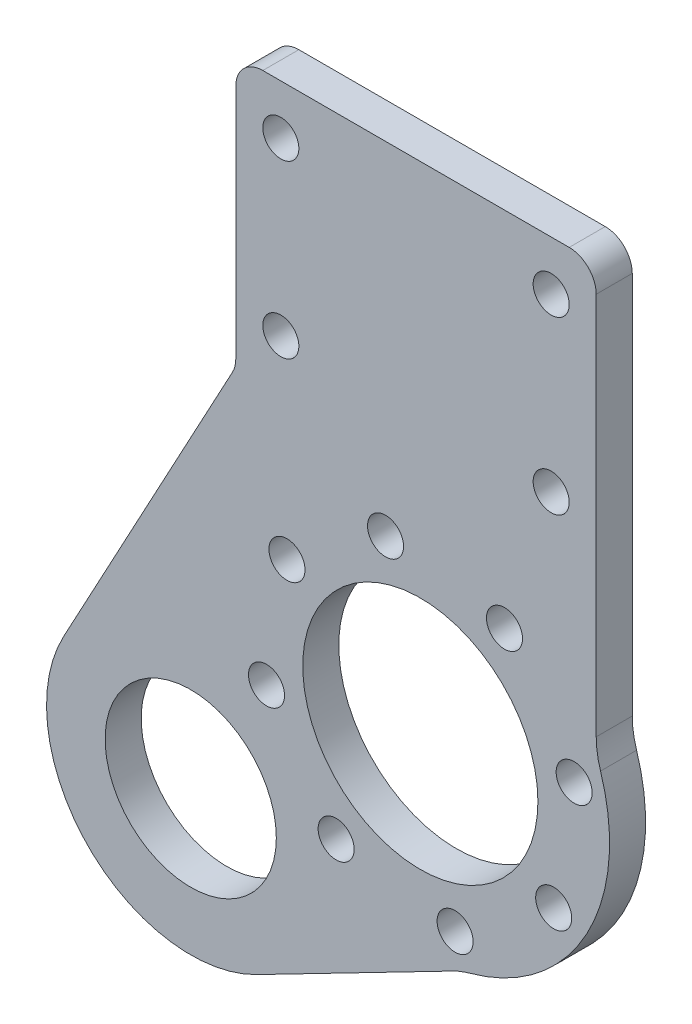
SolidWorks part; units mm, degrees
material "Thornel Mat VMA"
ref_plane "前视基准面" through (0, 0, 0) normal (0, 0, 1) x (1, 0, 0)
ref_plane "上视基准面" through (0, 0, 0) normal (0, 1, 0) x (1, 0, 0)
ref_plane "右视基准面" through (0, 0, 0) normal (1, 0, 0) x (0, 0, -1)
sketch "草图1" plane through (0, 0, 0) normal (0, 0, 1) x (1, 0, 0)
  line L0 (-30.2639, 43) -> (71.8423, 43) construction
  line L1 (-16, 73) -> (-16, 0)
  line L2 (-16, 73) -> (45, 73)
  line L3 (45, 73) -> (45, 18)
  line L4 (7.3324, -14.221) -> (33.6238, -0.665)
  circle A0 centre (0, 0) radius 10 construction
  arc A1 (33.6238, -0.665) -> (45, 18) centre (24, 18) ccw
  circle A2 centre (24, 18) radius 20 construction
  circle A3 centre (24, 18) radius 13.05
  circle A5 centre (0, 0) radius 9.5
  arc A6 (-16, 0) -> (7.3324, -14.221) centre (0, 0) ccw
  dimension "D1" = 20
  dimension "D2" = 42
  dimension "D3" = 40
  dimension "D5" = 4
  dimension "D6" = 26.1
  dimension "D8" = 16
  dimension "D9" = 19
  dimension "D4" = 43
  dimension "D7" = 30
extrude "凸台-拉伸1" add sketch "草图1" along normal blind 4
fillet "圆角1" radius 3 2 edges at (45, 73, 2) (-16, 73, 2)
sketch "草图2" plane through (0, 0, 4) normal (0, 0, 1) x (1, 0, 0)
  line L0 (-14.0845, 7.5912) -> (5, 43)
  line L1 (5, 43) -> (5, 73)
  line L2 (42, 73) -> (-13, 73) construction
  line L4 (45, 18) -> (45, 70) construction
  line L5 (-16, 70) -> (-16, 0) construction
  line L6 (-16, 73) -> (-16, 0)
  line L7 (-16, 73) -> (5, 73)
  arc A1 (-14.0845, 7.5912) -> (-16, 0) centre (0, 0) ccw
  dimension "D2" = 30
  dimension "D3" = 40
extrude "切除-拉伸1" cut sketch "草图2" against normal blind 10
sketch "草图3" plane through (0, 0, 4) normal (0, 0, 1) x (1, 0, 0)
  line L0 (24, 18) -> (0, 0) construction
  circle A0 centre (24, 18) radius 17.5 construction
  circle A1 centre (8.9417, 26.9161) radius 2
  circle A2 centre (19.6568, 34.9525) radius 2
  circle A3 centre (32.9161, 33.0583) radius 2
  circle A4 centre (40.9525, 22.3432) radius 2
  circle A5 centre (39.0583, 9.0839) radius 2
  circle A6 centre (28.3432, 1.0475) radius 2
  circle A7 centre (15.0839, 2.9417) radius 2
  circle A8 centre (7.0475, 13.6568) radius 2
  point P22 (24, 18)
  dimension "D1" = 35
  dimension "D2" = 4
  dimension "D3" = 8
extrude "切除-拉伸2" cut sketch "草图3" against normal blind 10
fillet "圆角2" radius 3 2 edges at (5, 43, 2) (5, 73, 2)
sketch "草图4" plane through (0, 0, 4) normal (0, 0, 1) x (1, 0, 0)
  line L0 (45, 18) -> (45, 70) construction
  line L1 (10, 48.5) -> (40, 48.5) construction
  line L2 (10, 48.5) -> (10, 67.5) construction
  line L3 (10, 67.5) -> (40, 67.5) construction
  line L4 (40, 48.5) -> (40, 67.5) construction
  line L5 (25, 67.5) -> (25, 48.5) construction
  line L6 (10, 58) -> (40, 58) construction
  line L7 (25, 67.5) -> (25, 73) construction
  line L8 (42, 73) -> (8, 73) construction
  circle A0 centre (40, 67.5) radius 2
  circle A1 centre (10, 67.5) radius 2
  circle A2 centre (10, 48.5) radius 2
  circle A3 centre (40, 48.5) radius 2
  point P0 (25, 58)
  dimension "D4" = 4
  dimension "D1" = 5
  dimension "D2" = 5.5
  dimension "D3" = 19
extrude "切除-拉伸3" cut sketch "草图4" against normal blind 28
sketch "草图6" plane through (0, 0, 4) normal (0, 0, 1) x (1, 0, 0)
  circle A0 centre (24, 18) radius 20.45
  dimension "D1" = 40.9
extrude "凸台-拉伸2" add sketch "草图6" against normal up to surface (4 mm away) up to face at (42, 48.5, 0)
sketch "草图7" plane through (0, 0, 4) normal (0, 0, 1) x (1, 0, 0)
  line L0 (24, 18) -> (25.48, 18) construction
  circle A0 centre (25.48, 18) radius 21
  dimension "D2" = 42
  dimension "D1" = 1.48
extrude "凸台-拉伸3" add sketch "草图7" against normal up to surface (4 mm away) up to face at (42, 48.5, 0)
sketch "草图8" plane through (0, 0, 4) normal (0, 0, 1) x (1, 0, 0)
  circle A0 centre (25.48, 18) radius 13.05
  dimension "D1" = 26.1
extrude "切除-拉伸4" cut sketch "草图8" against normal up to surface (4 mm away) up to face at (42, 48.5, 0)
sketch "草图9" plane through (0, 0, 4) normal (0, 0, 1) x (1, 0, 0)
  line L0 (0, 0) -> (25.48, 18) construction
  circle A0 centre (25.48, 18) radius 17.5 construction
  circle A1 centre (10.6816, 27.3412) radius 2
  circle A2 centre (21.6211, 35.0692) radius 2
  circle A3 centre (34.8212, 32.7984) radius 2
  circle A4 centre (42.5492, 21.8589) radius 2
  circle A5 centre (40.2784, 8.6588) radius 2
  circle A6 centre (29.3389, 0.9308) radius 2
  circle A7 centre (16.1388, 3.2016) radius 2
  circle A8 centre (8.4108, 14.1411) radius 2
  point P5 (17.0751, 2.3972)
  point P21 (25.48, 18)
  dimension "D1" = 35
  dimension "D2" = 4
  dimension "D3" = 8
extrude "切除-拉伸5" cut sketch "草图9" against normal up to surface (4 mm away) up to face at (38.53, 18, 0)
fillet "圆角3" radius 10 2 edges at (30.0876, -2.4883, 2) (45, 25.744, 2)
